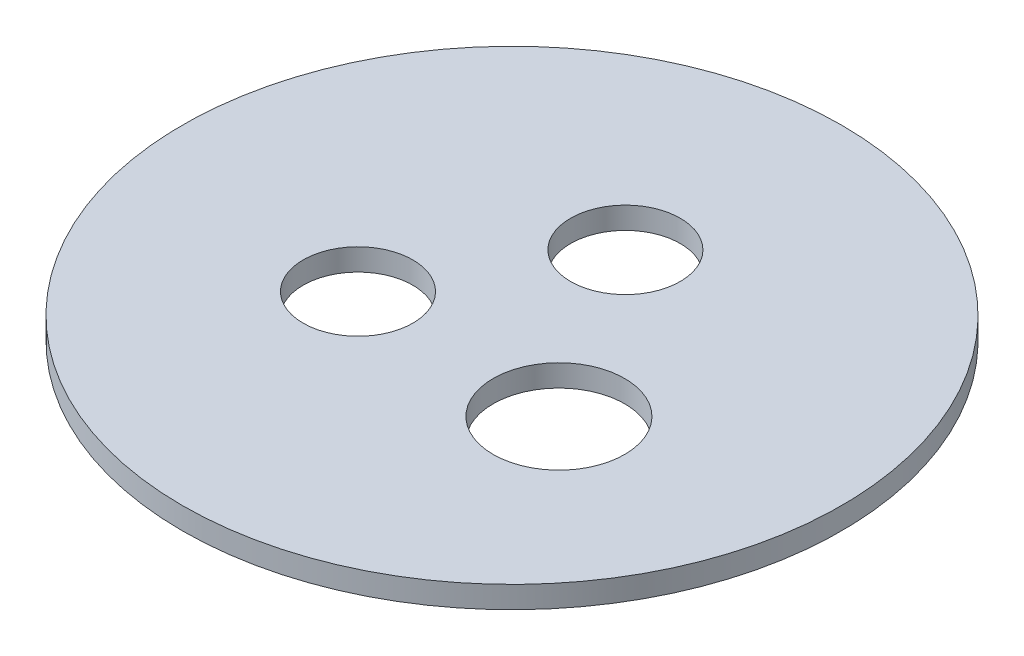
SolidWorks part; units mm, degrees
ref_plane "Front Plane" through (0, 0, 0) normal (0, 0, 1) x (1, 0, 0)
ref_plane "Top Plane" through (0, 0, 0) normal (0, 1, 0) x (1, 0, 0)
ref_plane "Right Plane" through (0, 0, 0) normal (1, 0, 0) x (0, 0, -1)
sketch "Sketch1" plane through (0, 0, 0) normal (0, 1, 0) x (1, 0, 0)
  circle A0 centre (0, 0) radius 30.05
  dimension "D1" = 60.1
extrude "Boss-Extrude1" add sketch "Sketch1" along normal blind 2
sketch "Sketch2" plane through (0, 2, 0) normal (0, 1, 0) x (1, 0, 0)
  line L0 (0, 0) -> (0, 30.05) construction
  line L1 (0, 0) -> (-26.0241, -15.025) construction
  line L2 (0, 0) -> (26.0241, -15.025) construction
  circle A0 centre (-8.9027, -5.1399) radius 8 construction
  circle A1 centre (0, 10.3419) radius 8 construction
  circle A2 centre (10.1251, -5.8457) radius 9 construction
  circle A3 centre (0, 0) radius 30.05 construction
  circle A4 centre (0, 10.3419) radius 5
  circle A5 centre (-8.9027, -5.1399) radius 5
  circle A6 centre (10.1251, -5.8457) radius 6
  dimension "D1" = 16
  dimension "D2" = 16
  dimension "D3" = 18
  dimension "D6" = 10
  dimension "D7" = 10
  dimension "D8" = 12
  dimension "D4" = 120
  dimension "D5" = 120
extrude "Cut-Extrude1" cut sketch "Sketch2" against normal blind 2
